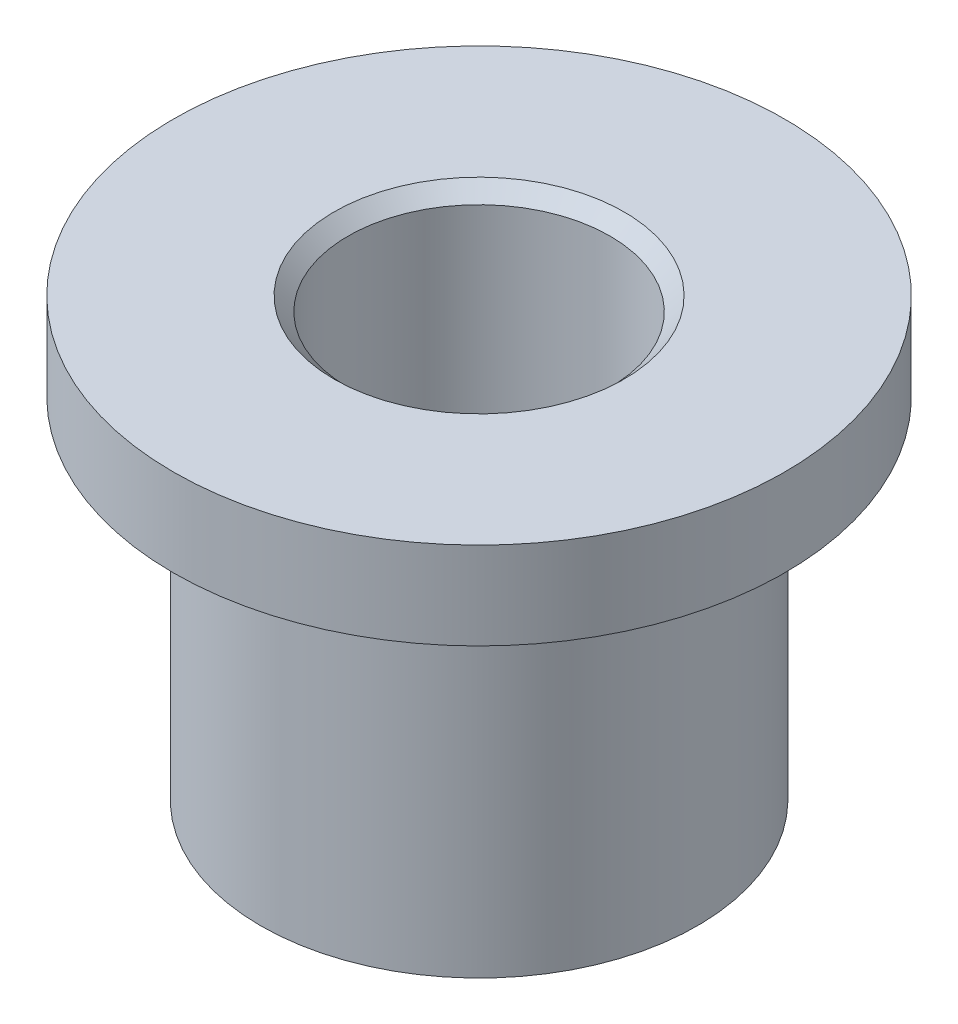
SolidWorks part; units mm, degrees
material "Tin Bearing Bronze"
ref_plane "Front Plane" through (0, 0, 0) normal (0, 0, 1) x (1, 0, 0)
ref_plane "Top Plane" through (0, 0, 0) normal (0, 1, 0) x (1, 0, 0)
ref_plane "Right Plane" through (0, 0, 0) normal (1, 0, 0) x (0, 0, -1)
sketch "Sketch1" plane through (0, 0, 0) normal (0, 0, 1) x (1, 0, 0)
  line L0 (-2.3813, 3.9688) -> (-5.5562, 3.9688)
  line L1 (-5.5562, 3.9688) -> (-5.5562, 2.3812)
  line L2 (-5.5562, 2.3812) -> (-3.9688, 2.3812)
  line L3 (-3.9688, 2.3812) -> (-3.9687, -3.9688)
  line L4 (-3.9687, -3.9688) -> (-2.3813, -3.9688)
  line L5 (-2.3813, -3.9688) -> (-2.3813, 3.9688)
  line L6 (0, 6.35) -> (0, -6.35) construction
  point P2 (-2.3813, 0)
  dimension "D1" = 7.9375
  dimension "D2" = 2.3813
  dimension "D3" = 3.9688
  dimension "D4" = 1.5875
  dimension "D5" = 11.1125
revolve "Revolve1" add sketch "Sketch1" angle 360 about L6
chamfer "Chamfer1" distance 0.254 angle 45 2 edges at (0, 3.9688, 2.3813) (0, -3.9688, 2.3813)
